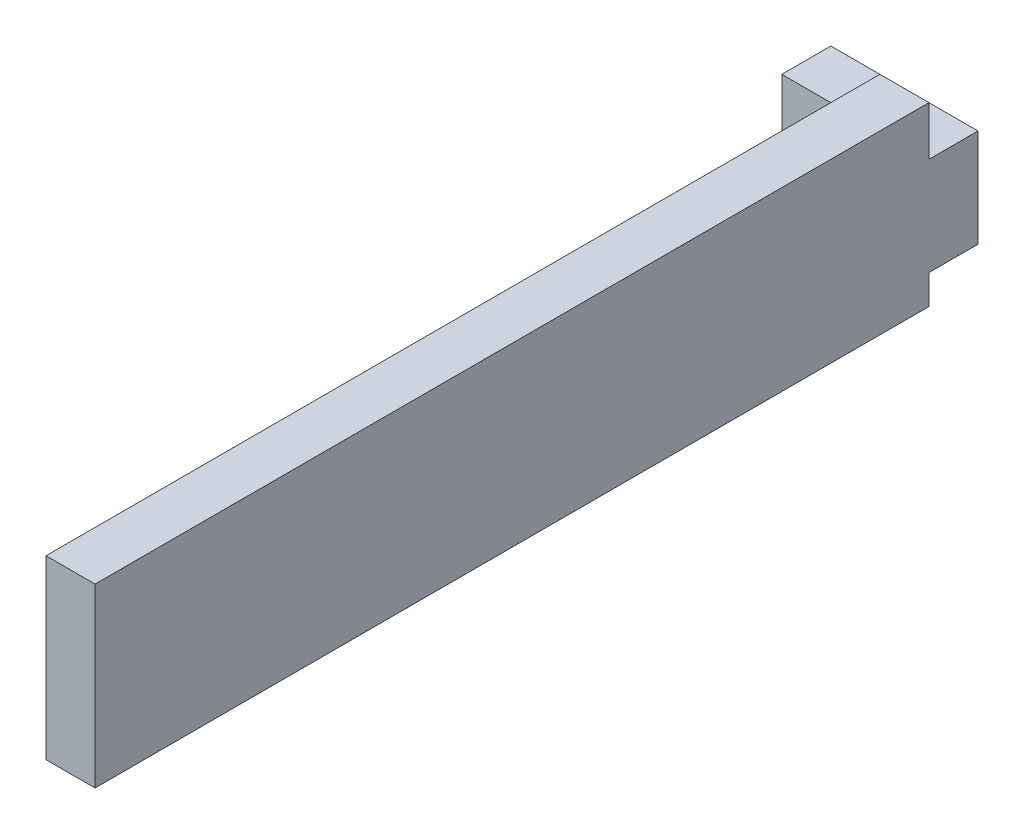
SolidWorks part; units mm, degrees
ref_plane "Front Plane" through (0, 0, 0) normal (0, 0, 1) x (1, 0, 0)
ref_plane "Top Plane" through (0, 0, 0) normal (0, 1, 0) x (1, 0, 0)
ref_plane "Right Plane" through (0, 0, 0) normal (1, 0, 0) x (0, 0, -1)
sketch "Sketch1" plane through (0, 0, 0) normal (0, 1, 0) x (1, 0, 0)
  line L5 (5, -5) -> (10, -5)
  line L6 (5, -5) -> (5, 0)
  line L9 (5, 0) -> (5, -5) construction
  line L10 (20, -90) -> (15, -90)
  line L11 (15, -90) -> (15, -5)
  line L12 (20, 0) -> (20, -90)
  line L13 (10, 0) -> (20, 0)
  line L14 (15, -5) -> (10, -5)
  line L16 (10, 0) -> (5, 0)
  dimension "D3" = 5
  dimension "D4" = 5
  dimension "D5" = 5
  dimension "D6" = 90
  dimension "D7" = 85
  dimension "D8" = 5
extrude "Boss-Extrude1" add sketch "Sketch1" along normal blind 10
ref_plane "Plane1" through (0, 10, 0) normal (0, 1, 0) x (1, 0, 0)
sketch "Sketch2" plane through (0, 10, 0) normal (0, 1, 0) x (1, 0, 0)
  line L1 (15, -5) -> (20, -5)
  line L2 (15, -5) -> (15, -90)
  line L3 (15, -90) -> (20, -90)
  line L4 (20, -5) -> (20, -90)
extrude "Boss-Extrude2" add sketch "Sketch2" along normal blind 5
ref_plane "Plane2" through (0, 0, 0) normal (0, -1, 0) x (-1, 0, 0)
sketch "Sketch4" plane through (0, 0, 0) normal (0, -1, 0) x (-1, 0, 0)
  line L1 (-15, -5) -> (-20, -5)
  line L2 (-15, -5) -> (-15, -90)
  line L3 (-15, -90) -> (-20, -90)
  line L4 (-20, -5) -> (-20, -90)
extrude "Boss-Extrude4" add sketch "Sketch4" along normal blind 3
